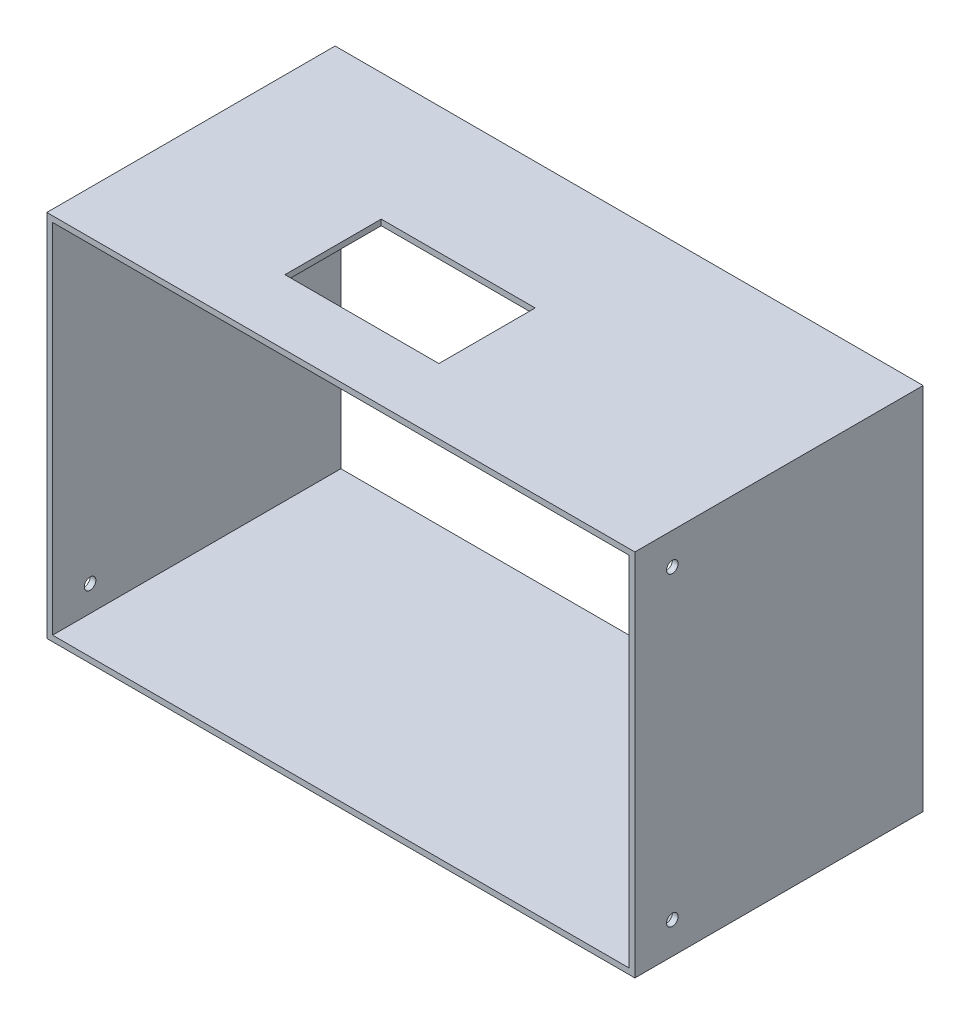
SolidWorks part; units mm, degrees
ref_plane "Спереди" through (0, 0, 0) normal (0, 0, 1) x (1, 0, 0)
ref_plane "Сверху" through (0, 0, 0) normal (0, 1, 0) x (1, 0, 0)
ref_plane "Справа" through (0, 0, 0) normal (1, 0, 0) x (0, 0, -1)
sketch "Эскиз1" plane through (0, 0, 0) normal (0, 0, 1) x (1, 0, 0)
  line L0 (2, 66) -> (2, 2)
  line L1 (2, 2) -> (104, 2)
  line L2 (104, 2) -> (104, 66)
  line L3 (104, 66) -> (2, 66)
  line L13 (3, 65) -> (103, 65)
  line L14 (103, 65) -> (103, 3)
  line L15 (103, 3) -> (3, 3)
  line L16 (3, 3) -> (3, 65)
  dimension "D8" = 1
  dimension "D10" = 1
  dimension "D9" = 1
  dimension "D1" = 64
  dimension "D2" = 102
  dimension "D7" = 1
extrude "Бобышка-Вытянуть1" add sketch "Эскиз1" along normal blind 50
sketch "Эскиз4" plane through (0, 66, 0) normal (0, 1, 0) x (1, 0, 0)
  line L0 (2, 0) -> (2, 1)
  line L1 (2, 0) -> (104, 0)
  line L2 (104, 0) -> (104, 1)
  line L3 (2, 1) -> (104, 1)
sketch "Эскиз5" plane through (103, 0, 0) normal (-1, 0, 0) x (0, 0, 1)
  circle A0 centre (43.5, 7.5) radius 1
  circle A1 centre (43.5, 60.5) radius 1
extrude "Вырез-Вытянуть2" cut sketch "Эскиз5" along normal blind 102 and the other way blind 1
sketch "Эскиз7" plane through (2, 0, 0) normal (-1, 0, 0) x (0, 0, 1)
  line L0 (0, 61) -> (12, 61) construction
  line L1 (0, 66) -> (0, 2) construction
  line L2 (12, 61) -> (12, 66) construction
  line L3 (50, 66) -> (0, 66) construction
  line L6 (12, 61) -> (20.5, 61)
  line L7 (12, 61) -> (12, 52.5)
  line L8 (12, 52.5) -> (20.5, 52.5)
  line L9 (20.5, 61) -> (20.5, 52.5)
  point P8 (12, 61)
  dimension "D1" = 12
  dimension "D2" = 5
  dimension "D3" = 8.5
  dimension "D4" = 8.5
extrude "Вырез-Вытянуть4" cut sketch "Эскиз7" against normal blind 10 contours L7 L6 L9 L8
sketch "Эскиз8" plane through (0, 66, 0) normal (0, 1, 0) x (1, 0, 0)
  line L0 (2, -38.7) -> (32, -38.7) construction
  line L1 (2, -50) -> (2, 0) construction
  line L2 (32, -38.7) -> (32, -50) construction
  line L3 (104, -50) -> (2, -50) construction
  line L5 (32, -38.7) -> (58.7, -38.7)
  line L6 (32, -38.7) -> (32, -22)
  line L7 (32, -22) -> (58.7, -22)
  line L8 (58.7, -38.7) -> (58.7, -22)
  point P8 (32, -38.7)
  dimension "D1" = 30
  dimension "D2" = 11.3
  dimension "D3" = 26.7
  dimension "D4" = 16.7
extrude "Вырез-Вытянуть5" cut sketch "Эскиз8" against normal blind 10 contours L6 L5 L8 L7
